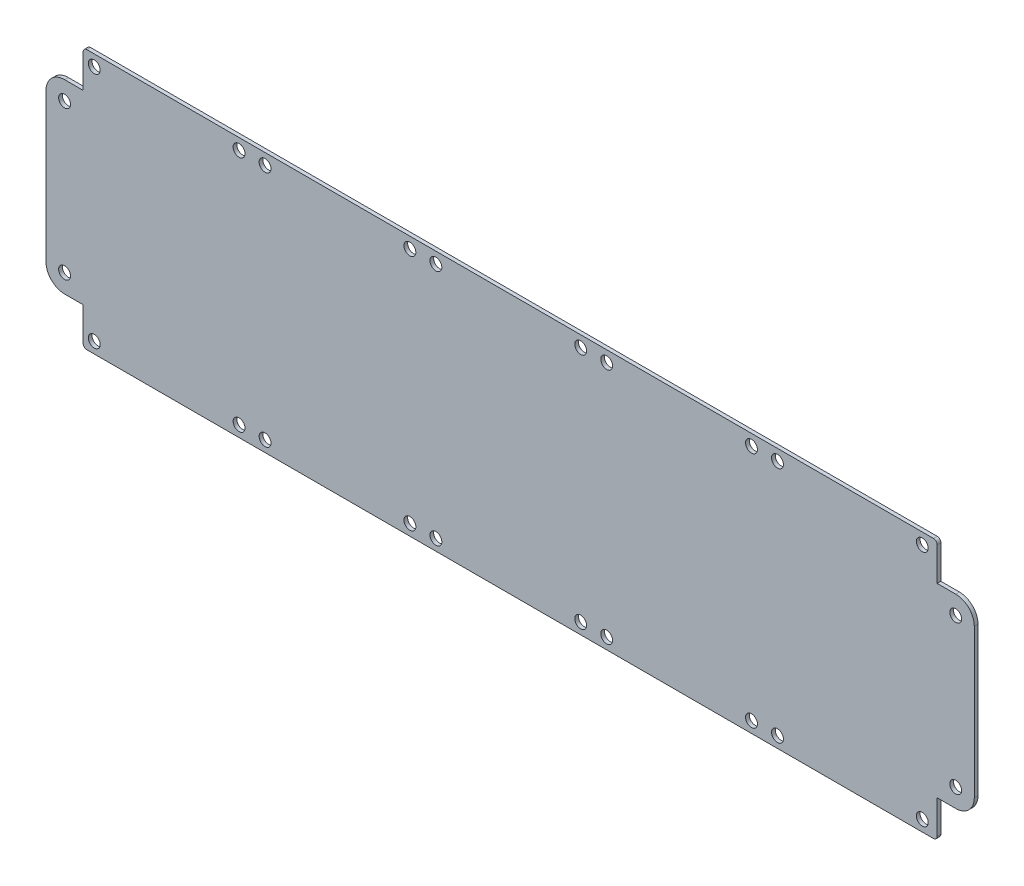
SolidWorks part; units mm, degrees
ref_plane "Front Plane" through (0, 0, 0) normal (0, 0, 1) x (1, 0, 0)
ref_plane "Top Plane" through (0, 0, 0) normal (0, 1, 0) x (1, 0, 0)
ref_plane "Right Plane" through (0, 0, 0) normal (1, 0, 0) x (0, 0, -1)
sketch "Sketch1" plane through (0, 0, 0) normal (0, 0, 1) x (1, 0, 0)
  line L0 (202.0857, -21.015) -> (202.0857, -30.015)
  line L1 (-26.9143, 38.985) -> (201.0857, 38.985)
  line L2 (-27.9143, 37.985) -> (-27.9143, 28.985)
  line L3 (-26.9143, -31.015) -> (201.0857, -31.015)
  line L4 (202.0857, 37.985) -> (202.0857, 28.985)
  line L7 (202.0857, 28.985) -> (207.0857, 28.985)
  line L9 (202.0857, -21.015) -> (207.0857, -21.015)
  line L10 (-27.9143, -21.015) -> (-27.9143, -30.015)
  line L11 (212.0857, 23.985) -> (212.0857, -16.015)
  line L12 (-27.9143, 28.985) -> (-32.9143, 28.985)
  line L14 (-27.9143, -21.015) -> (-32.9143, -21.015)
  line L15 (-37.9143, 23.985) -> (-37.9143, -16.015)
  circle A0 centre (-24.9143, 35.985) radius 1.6
  circle A1 centre (14.0857, 35.985) radius 1.6
  circle A2 centre (-24.9143, -28.015) radius 1.6
  circle A3 centre (14.0857, -28.015) radius 1.6
  circle A4 centre (21.0857, 35.985) radius 1.6
  circle A5 centre (60.0857, 35.985) radius 1.6
  circle A6 centre (60.0857, -28.015) radius 1.6
  circle A7 centre (21.0857, -28.015) radius 1.6
  circle A8 centre (67.0857, 35.985) radius 1.6
  circle A9 centre (106.0857, 35.985) radius 1.6
  circle A10 centre (106.0857, -28.015) radius 1.6
  circle A11 centre (67.0857, -28.015) radius 1.6
  circle A12 centre (113.0857, 35.985) radius 1.6
  circle A13 centre (152.0857, 35.985) radius 1.6
  circle A14 centre (152.0857, -28.015) radius 1.6
  circle A15 centre (113.0857, -28.015) radius 1.6
  circle A16 centre (159.0857, 35.985) radius 1.6
  circle A17 centre (198.0857, 35.985) radius 1.6
  circle A18 centre (198.0857, -28.015) radius 1.6
  circle A19 centre (159.0857, -28.015) radius 1.6
  arc A20 (207.0857, 28.985) -> (212.0857, 23.985) centre (207.0857, 23.985) cw
  arc A21 (207.0857, -21.015) -> (212.0857, -16.015) centre (207.0857, -16.015) ccw
  arc A22 (-32.9143, -21.015) -> (-37.9143, -16.015) centre (-32.9143, -16.015) cw
  arc A23 (-32.9143, 28.985) -> (-37.9143, 23.985) centre (-32.9143, 23.985) ccw
  circle A24 centre (-32.9143, -16.015) radius 1.6
  circle A25 centre (-32.9143, 23.985) radius 1.6
  circle A26 centre (207.0857, 23.985) radius 1.6
  circle A27 centre (207.0857, -16.015) radius 1.6
  arc A28 (201.0857, -31.015) -> (202.0857, -30.015) centre (201.0857, -30.015) ccw
  arc A29 (201.0857, 38.985) -> (202.0857, 37.985) centre (201.0857, 37.985) cw
  arc A30 (-27.9143, -30.015) -> (-26.9143, -31.015) centre (-26.9143, -30.015) ccw
  arc A31 (-26.9143, 38.985) -> (-27.9143, 37.985) centre (-26.9143, 37.985) ccw
  dimension "D3" = 3
  dimension "D4" = 3
  dimension "D5" = 39
  dimension "D6" = 3
  dimension "D7" = 39
  dimension "D8" = 39
  dimension "D9" = 39
  dimension "D10" = 39
  dimension "D11" = 39
  dimension "D12" = 39
  dimension "D14" = 7
  dimension "D15" = 7
  dimension "D16" = 7
  dimension "D17" = 7
  dimension "D18" = 7
  dimension "D19" = 7
  dimension "D20" = 3
  dimension "D21" = 3
  dimension "D22" = 3
  dimension "D23" = 3
  dimension "D25" = 3
  dimension "D26" = 3
  dimension "D27" = 3
  dimension "D28" = 3
  dimension "D29" = 3
  dimension "D30" = 3
  dimension "D31" = 3
  dimension "D32" = 3
  dimension "D35" = 7
  dimension "D36" = 39
  dimension "D37" = 7
  dimension "D38" = 39
  dimension "D45" = 5
  dimension "D46" = 1
  dimension "D1" = 230
  dimension "D2" = 70
  dimension "D13" = 39
  dimension "D24" = 3
  dimension "D33" = 3
  dimension "D34" = 3
  dimension "D39" = 10
  dimension "D40" = 10
  dimension "D41" = 10
  dimension "D42" = 10
  dimension "D43" = 10
  dimension "D44" = 10
extrude "Boss-Extrude1" add sketch "Sketch1" along normal blind 1
